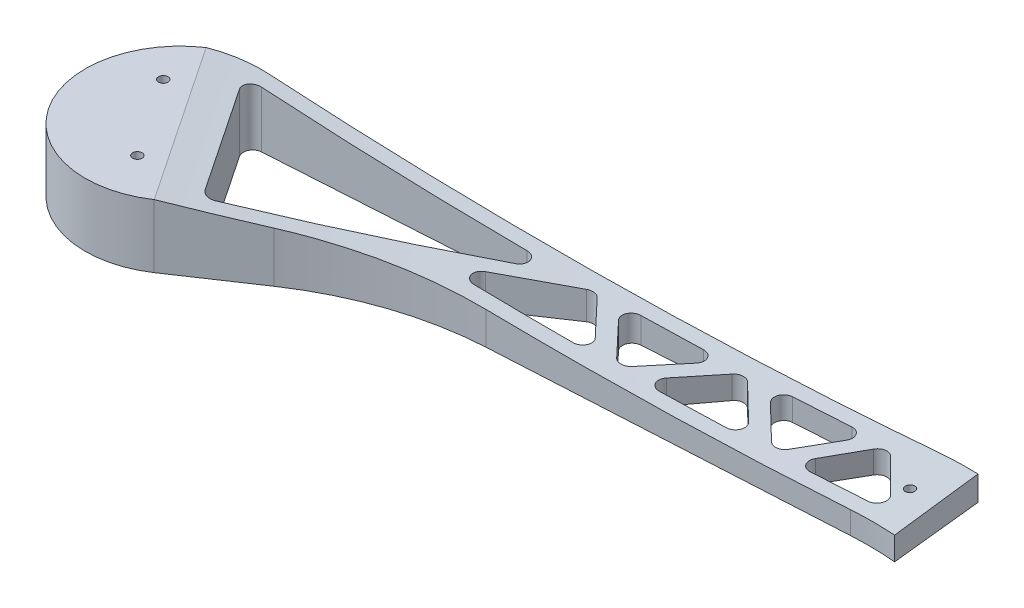
SolidWorks part; units mm, degrees
ref_plane "Front Plane" through (0, 0, 0) normal (0, 0, 1) x (1, 0, 0)
ref_plane "Top Plane" through (0, 0, 0) normal (0, 1, 0) x (1, 0, 0)
ref_plane "Right Plane" through (0, 0, 0) normal (1, 0, 0) x (0, 0, -1)
sketch "Sketch1" plane through (0, 0, 0) normal (0, 1, 0) x (1, 0, 0)
  line L0 (0, 0) -> (-350, 0) construction
  line L1 (0, 0) -> (40, 0) construction
  line L2 (0, 15) -> (40, 15)
  line L3 (0, -15) -> (40, -15)
  line L4 (-351.8754, 29.9413) -> (-333.2857, -24.9125) construction
  line L5 (-139.7849, 43.2259) -> (-4217.6379, -212.1962)
  line L6 (0, 15) -> (-4004.6012, 823.6244)
  line L7 (0, 15) -> (-5.9197, -13.7825) construction
  line L8 (-4217.6379, -212.1962) -> (-138.0533, 13.889)
  line L9 (-4004.6012, 823.6244) -> (-5.9197, -13.7825)
  line L10 (-333.2857, -24.9125) -> (-287.8235, 5.5889)
  line L11 (-5.9197, -13.7825) -> (0, -15)
  circle A0 centre (0, 0) radius 5
  circle A1 centre (-350, 0) radius 30
  circle A2 centre (40, 0) radius 2
  circle A3 centre (0, 0) radius 15
  circle A4 centre (40, 0) radius 15
  dimension "D1" = 10
  dimension "D4" = 4
  dimension "D5" = 60
  dimension "D6" = 30
  dimension "D7" = 165
  dimension "D2" = 350
  dimension "D3" = 40
  dimension "D8" = 165
  dimension "D9" = 135
  dimension "D10" = 150
extrude "Boss-Extrude1" add sketch "Sketch1" along normal blind 20 contours L8 A1 | A1 L8 | A1 L8 L9 L5 | A1 L10 L8 | A3 L6 L5 L9 | A3 A0 | A4 L2 A3 L3 | A4 A2
fillet "Fillet1" radius 100 5 edges at (0, 10, -15) (-139.7849, 10, -43.2259) (-138.0533, 10, -13.889) (-287.8235, 10, -5.5889) (0, 10, 15)
ref_plane "Plane1" through (-86.3568, 0, -128.7144) normal (0.5571, 0, 0.8304) x (0.8304, 0, -0.5571)
sketch "Sketch3" plane through (-86.3568, 0, -128.7144) normal (0.5571, 0, 0.8304) x (0.8304, 0, -0.5571)
  line L0 (-290.646, 20) -> (-290.646, 0) construction
  line L1 (-290.646, 20) -> (-263.3377, 20) construction
  line L2 (-290.646, 20) -> (0.1568, 20)
  line L4 (48.2167, 0) -> (48.2167, 20) construction
  line L5 (0.1568, 20) -> (48.2167, 20)
  line L6 (48.2167, 20) -> (48.2167, 10)
  line L11 (0.1568, 20) -> (0.1568, 0) construction
  line L13 (48.2167, 0) -> (48.2167, 20) construction
  line L14 (48.2167, 7) -> (-242.9986, 7) construction
  line L15 (-15.6816, 0) -> (-15.6816, 20) construction
  spline S0 degree 2 poles (-290.646, 20) (-152.5347, -2.5394) (-15.6816, 14) knots 0 0 0 1 1 1
  spline S1 degree 3 poles (-15.6816, 14) (1.7787, 1.081) (32.0315, 10) (48.2167, 10) knots 0 0 0 0 1 1 1 1
  point P4 (48.2167, 7)
  dimension "D2" = 6
  dimension "D1" = 10
  dimension "D3" = 7
extrude "Cut-Extrude3" cut sketch "Sketch3" along normal blind 300 and the other way blind 131
fillet "Fillet3" radius 5 1 edges at (-21.8644, 14, -4.4422)
sketch "Sketch4" plane through (0, 0, 0) normal (0, 1, 0) x (1, 0, 0)
  line L0 (-23.8661, -4.9157) -> (-39.1031, 17.7949)
  line L1 (-39.1031, 17.7949) -> (-75.6397, 5.9268)
  line L2 (-75.6397, 5.9268) -> (-23.8661, -4.9157)
  line L3 (-125.1676, 11.1905) -> (-12.8731, -12.3263) construction
  line L4 (-12.8731, -12.3263) -> (-36.0971, 22.2889) construction
  line L5 (-49.0834, 19.8102) -> (-105.8384, 31.2704)
  line L6 (-105.8384, 31.2704) -> (-85.48, 7.9875)
  line L7 (-85.48, 7.9875) -> (-49.0834, 19.8102)
  line L8 (-36.0971, 22.2889) -> (-126.8801, 40.6201) construction
  line L9 (-113.9044, 32.8991) -> (-93.6107, 9.6903)
  line L10 (-93.6107, 9.6903) -> (-134.1835, 18.1871)
  line L11 (-134.1835, 18.1871) -> (-113.9044, 32.8991)
  line L12 (-127.4003, 35.6242) -> (-14.8981, 12.9074) construction
  line L13 (-134.1835, 18.1871) -> (-23.8661, -4.9157) construction
  line L14 (-150.6827, 37.5335) -> (-354.5716, 24.7626) construction
  line L15 (-143.9898, 18.5677) -> (-279.6875, 11.0475) construction
  line L16 (-260.4276, 7.1072) -> (-151.1984, 13.1605) construction
  line L17 (-152.9244, 42.4029) -> (-351.8754, 29.9413) construction
  line L18 (-143.9898, 18.5677) -> (-162.2437, 36.8094)
  line L19 (-162.2437, 36.8094) -> (-173.6392, 16.9246)
  line L20 (-173.6392, 16.9246) -> (-143.9898, 18.5677)
  line L21 (-168.2211, 36.435) -> (-179.5911, 16.5947)
  line L22 (-179.5911, 16.5947) -> (-198.1353, 34.5613)
  line L23 (-198.1353, 34.5613) -> (-168.2211, 36.435)
  line L24 (-186.3879, 16.218) -> (-204.8846, 34.1385)
  line L25 (-204.8846, 34.1385) -> (-219.6625, 14.374)
  line L26 (-219.6625, 14.374) -> (-186.3879, 16.218)
  line L27 (-211.4344, 33.7282) -> (-226.1755, 14.0131)
  line L28 (-226.1755, 14.0131) -> (-242.9353, 31.7551)
  line L29 (-242.9353, 31.7551) -> (-211.4344, 33.7282)
  line L30 (-232.7115, 13.6509) -> (-279.6875, 11.0475)
  line L31 (-279.6875, 11.0475) -> (-249.4292, 31.3484)
  line L32 (-249.4292, 31.3484) -> (-232.7115, 13.6509)
  line L33 (-150.6827, 37.5335) -> (-143.9898, 18.5677) construction
  line L34 (-143.9898, 18.5677) -> (-134.1835, 18.1871) construction
  line L35 (-127.4003, 35.6242) -> (-134.1835, 18.1871) construction
  line L37 (-259.3276, 30.7284) -> (-327.7673, -15.189)
  line L38 (-327.7673, -15.189) -> (-354.5716, 24.7626)
  line L39 (-366.7143, 24.9125) -> (-333.2857, -24.9125) construction
  line L40 (-333.2857, -24.9125) -> (-310.6084, -9.6979) construction
  line L41 (-354.5716, 24.7626) -> (-259.3276, 30.7284)
  line L42 (-364.7467, 9.4158) -> (-348.0325, -15.4967) construction
  circle A0 centre (-147.3362, 28.0506) radius 1.5
  circle A1 centre (-130.7919, 26.9057) radius 1.5
  circle A2 centre (-364.7467, 9.4158) radius 1.5
  circle A3 centre (-348.0325, -15.4967) radius 1.5
  dimension "D12" = 3
  dimension "D13" = 3
  dimension "D1" = 5
  dimension "D2" = 5
  dimension "D3" = 5
  dimension "D4" = 5
  dimension "D5" = 5
  dimension "D6" = 5
  dimension "D7" = 5
  dimension "D8" = 5
  dimension "D9" = 5
  dimension "D10" = 5
  dimension "D11" = 5
  dimension "D14" = 10
  dimension "D15" = 5
  dimension "D16" = 5
  dimension "D17" = 7
  dimension "D18" = 30
extrude "Cut-Extrude4" cut sketch "Sketch4" along normal blind 114 contours L41 L37 L38 | L32 L30 L31 | L29 L27 L28 | L26 L24 L25 | L23 L21 L22 | L20 L18 L19 | A1 | A0 | L11 L9 L10 | L7 L5 L6 | L2 L0 L1 | A3 | A2
fillet "Fillet4" radius 3 27 edges at (-23.8661, 6.5969, 4.9157) (-75.6397, 4.8538, -5.9268) (-39.1031, 6.5969, -17.7949) (-49.0834, 6.2031, -19.8102) (-85.48, 4.6031, -7.9875) (-105.8384, 4.4739, -31.2704) (-93.6107, 4.4153, -9.6903) (-134.1835, 3.7402, -18.1871) (-113.9044, 4.2984, -32.8991) (-143.9898, 3.6314, -18.5677) (-173.6392, 3.5024, -16.9246) (-162.2437, 3.5795, -36.8094) (-179.5911, 3.5172, -16.5947) (-198.1353, 3.5474, -34.5613) (-168.2211, 3.5395, -36.435) (-204.8846, 3.5971, -34.1385) (-186.3879, 3.5507, -16.218) (-219.6625, 3.9702, -14.374) (-242.9353, 4.2066, -31.7551) (-226.1755, 4.1019, -14.0131) (-211.4344, 3.6621, -33.7282) (-279.6875, 5.7968, -11.0475) (-232.7115, 4.2504, -13.6509) (-249.4292, 4.3664, -31.3484) (-259.3276, 4.6413, -30.7284) (-354.5716, 9.2095, -24.7626) (-327.7673, 9.2095, 15.189)
sketch "Sketch5" plane through (0, 0, 0) normal (0, 1, 0) x (1, 0, 0)
  line L0 (0, 156.2161) -> (0, 0) construction
  line L1 (0, 0) -> (-11.052, 105.1529) construction
  line L2 (-149.225, 128.2664) -> (-126.0115, -92.5949)
  line L3 (-149.225, 128.2664) -> (52.276, 176.4087)
  line L4 (52.276, 176.4087) -> (104.7262, -43.1237)
  line L5 (104.7262, -43.1237) -> (-126.0115, -92.5949)
  dimension "D1" = 6
  dimension "D2" = 135
extrude "Cut-Extrude5" cut sketch "Sketch5" along normal blind 83
